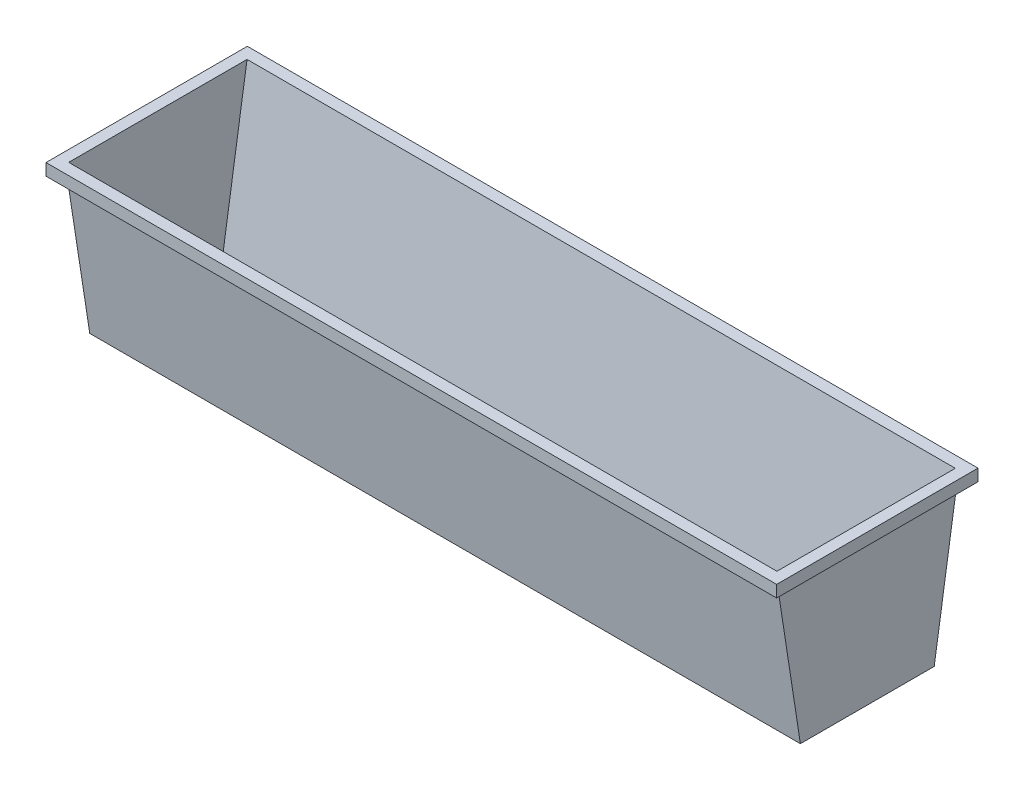
SolidWorks part; units mm, degrees
ref_plane "Front" through (0, 0, 0) normal (0, 0, 1) x (1, 0, 0)
ref_plane "Top" through (0, 0, 0) normal (0, 1, 0) x (1, 0, 0)
ref_plane "Right" through (0, 0, 0) normal (1, 0, 0) x (0, 0, -1)
sketch "Sketch1" plane through (0, 0, 0) normal (1, 0, 0) x (0, 0, -1)
  line L0 (0, 0) -> (113, 0)
  line L2 (141.5, 130) -> (-28.5, 130) construction
  line L4 (56.5, 0) -> (56.5, 130) construction
  line L5 (-28.5, 130) -> (-28.5, 120) construction
  line L6 (-28.5, 120) -> (-18.5, 120) construction
  line L7 (-20.0417, 130) -> (0, 0)
  line L8 (141.5, 130) -> (141.5, 120)
  line L9 (141.5, 120) -> (131.5, 120)
  line L10 (133.0417, 130) -> (113, 0)
  line L11 (-20.0417, 130) -> (133.0417, 130)
  dimension "D1" = 113
  dimension "D2" = 170
  dimension "D3" = 130
  dimension "D4" = 10
  dimension "D5" = 10
  dimension "D6" = 10
  dimension "D7" = 10
  dimension "D8" = 8.4583
  dimension "D9" = 8.4583
extrude "Boss-Extrude1" add sketch "Sketch1" against normal mid plane 600 contours L11 L10 L0 L7
sketch "Sketch2" plane through (0, 130, 0) normal (0, 1, 0) x (1, 0, 0)
  line L28 (308.4583, -28.5) -> (308.4583, 141.5)
  line L29 (-308.4583, -28.5) -> (308.4583, -28.5)
  line L30 (-308.4583, 141.5) -> (-308.4583, -28.5)
  line L31 (308.4583, 141.5) -> (-308.4583, 141.5)
  line L32 (308.4583, -28.5) -> (308.4583, 141.5)
  line L33 (-308.4583, -28.5) -> (308.4583, -28.5)
  line L34 (-308.4583, 141.5) -> (-308.4583, -28.5)
  line L35 (308.4583, 141.5) -> (-308.4583, 141.5)
  dimension "D1" = 8.4583
extrude "Boss-Extrude2" add sketch "Sketch2" along normal mid plane 10
sketch "Sketch3" plane through (-300, 0, 0) normal (-1, 0, 0) x (0, 0, 1)
  line L13 (-131.7889, 135) -> (18.7889, 135)
  line L14 (-141.5, 135) -> (28.5, 135) construction
  line L16 (-1.7153, 2) -> (17.2942, 125.3047)
  line L17 (-111.2847, 2) -> (-1.7153, 2)
  line L18 (-130.2942, 125.3047) -> (-111.2847, 2)
  line L19 (-1.7153, 2) -> (18.7889, 135)
  line L20 (-111.2847, 2) -> (-1.7153, 2)
  line L21 (-131.7889, 135) -> (-111.2847, 2)
  dimension "D1" = 2
extrude "Cut-Extrude1" cut sketch "Sketch3" against normal mid plane 598 from offset 300
